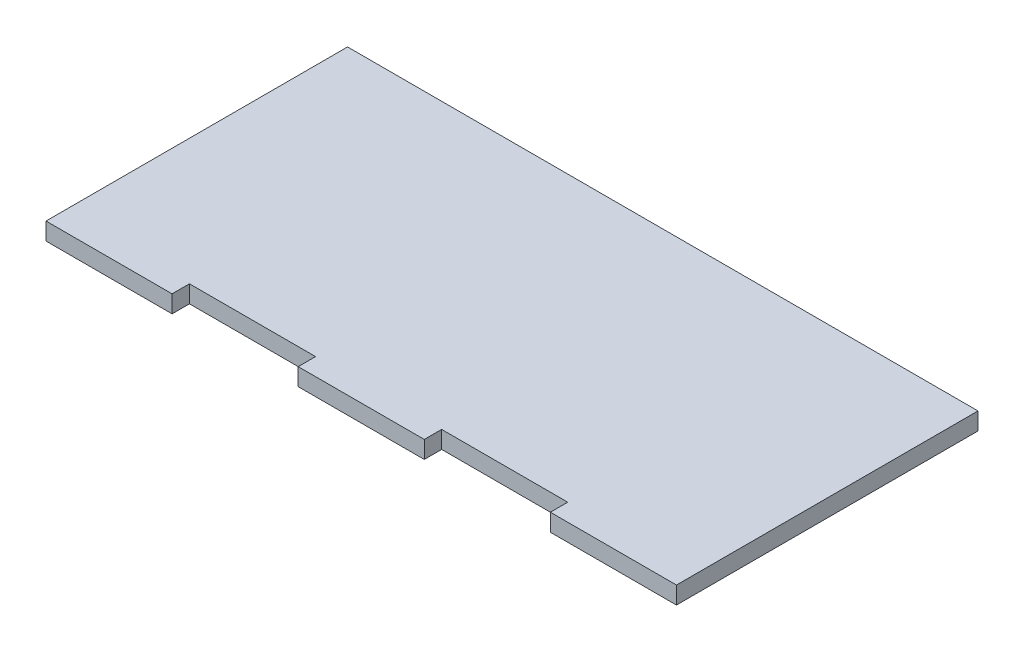
SolidWorks part; units mm, degrees
ref_plane "Front Plane" through (0, 0, 0) normal (0, 0, 1) x (1, 0, 0)
ref_plane "Top Plane" through (0, 0, 0) normal (0, 1, 0) x (1, 0, 0)
ref_plane "Right Plane" through (0, 0, 0) normal (1, 0, 0) x (0, 0, -1)
sketch "Sketch1" plane through (0, 0, 0) normal (0, 1, 0) x (1, 0, 0)
  line L1 (-69.721, 172.7566) -> (284.2839, 172.7566)
  line L2 (-69.721, 172.7566) -> (-69.721, 3.4402)
  line L3 (-69.721, 3.4402) -> (284.2839, 3.4402)
  line L4 (284.2839, 172.7566) -> (284.2839, 3.4402)
  dimension "D1" = 354.0049
  dimension "D2" = 169.3164
extrude "Boss-Extrude1" add sketch "Sketch1" along normal blind 9.7536
sketch "Sketch2" plane through (0, 0, 0) normal (0, -1, 0) x (1, 0, 0)
  line L0 (107.2814, -3.4402) -> (107.2814, -172.7566) construction
  line L1 (-69.721, -3.4402) -> (284.2839, -3.4402) construction
  line L2 (284.2839, -172.7566) -> (-69.721, -172.7566) construction
  line L3 (213.4829, -13.1938) -> (142.6819, -13.1938)
  line L4 (-69.721, -172.7566) -> (-69.721, -3.4402) construction
  line L6 (142.6819, -3.4402) -> (142.6819, -13.1938)
  line L7 (1.08, -3.4402) -> (71.881, -3.4402)
  line L8 (1.08, -3.4402) -> (1.08, -13.1938)
  line L9 (1.08, -13.1938) -> (71.881, -13.1938)
  line L10 (71.881, -3.4402) -> (71.881, -13.1938)
  line L11 (213.4829, -3.4402) -> (142.6819, -3.4402)
  line L12 (213.4829, -3.4402) -> (213.4829, -13.1938)
  dimension "D1" = 9.7536
  dimension "D2" = 70.801
  dimension "D3" = 70.801
extrude "Cut-Extrude1" cut sketch "Sketch2" against normal through all
equation "\"D1@Sketch1\"=\"Base Length@Assembled Container.Assembly\""
equation "\"D2@Sketch1\"=\"Side Height@Assembled Container.Assembly\""
equation "\"D1@Boss-Extrude1\"=\"Acrylic Thickness@Assembled Container.Assembly\""
equation "\"D1@Sketch2\"=\"Acrylic Thickness@Assembled Container.Assembly\""
equation "\"D2@Sketch2\"=\"Lid Long Side Outer Cutout@Assembled Container.Assembly\""
equation "\"D3@Sketch2\"=\"Lid Long Side Overhang@Assembled Container.Assembly\""
